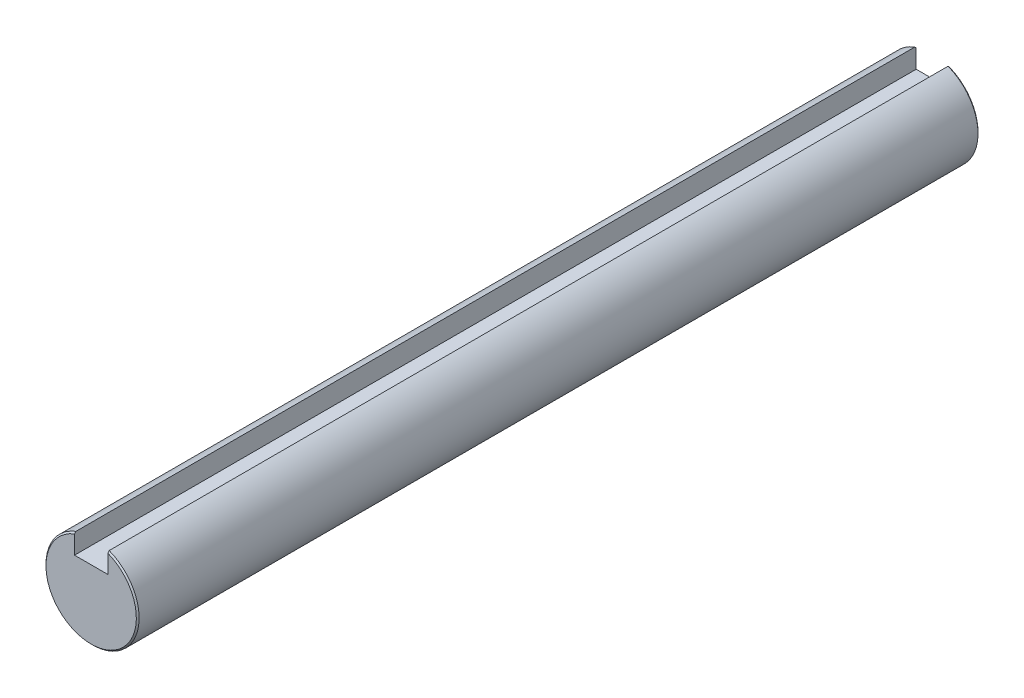
SolidWorks part; units mm, degrees
material "AISI 1045 Steel, cold drawn"
ref_plane "Front Plane" through (0, 0, 0) normal (0, 0, 1) x (1, 0, 0)
ref_plane "Top Plane" through (0, 0, 0) normal (0, 1, 0) x (1, 0, 0)
ref_plane "Right Plane" through (0, 0, 0) normal (1, 0, 0) x (0, 0, -1)
sketch "Sketch1" plane through (0, 0, 0) normal (1, 0, 0) x (0, 0, -1)
  line L0 (0, 0) -> (0, 7) construction
  line L1 (-63.25, 7) -> (63.25, 7)
  line L2 (-63.25, 7) -> (-63.25, -7)
  line L3 (-63.25, -7) -> (63.25, -7)
  line L4 (63.25, 7) -> (63.25, -7)
  line L5 (-63.25, 7) -> (63.25, -7) construction
  line L6 (-63.25, -7) -> (63.25, 7) construction
  line L7 (0, 0) -> (0, -7) construction
  point P0 (0, 0)
  point P8 (-47.15, 7)
  point P10 (47.15, 7)
  point P11 (-63.25, 0)
  dimension "Diameter" = 14
  dimension "Length" = 126.5
  dimension "D1" = 16.1
  dimension "D2" = 16.1
  dimension "Keyway Length" = 126.5
sketch "Sketch2" plane through (0, 0, 0) normal (0, 0, 1) x (1, 0, 0)
  line L0 (0, 0) -> (0, 7) construction
  line L2 (2.5, 3.5383) -> (-2.5, 3.5383)
  line L3 (2.5, 3.5383) -> (2.5, 6.5383)
  line L4 (2.5, 6.5383) -> (-2.5, 6.5383)
  line L5 (-2.5, 3.5383) -> (-2.5, 6.5383)
  line L6 (2.5, 3.5383) -> (-2.5, 6.5383) construction
  line L7 (2.5, 6.5383) -> (-2.5, 3.5383) construction
  circle A0 centre (0, 0) radius 7
  point P3 (0, 5.0383)
  dimension "Keyway Width" = 5
  dimension "Keyway Depth" = 3
sketch "Sketch3" plane through (0, 0, 0) normal (0, 0, 1) x (1, 0, 0)
  line L1 (-2.5, 3.5383) -> (-2.5, 6.5383) construction
  line L2 (2.5, 3.5383) -> (-2.5, 3.5383) construction
  line L3 (2.5, 3.5383) -> (2.5, 6.5383) construction
  line L5 (-2.5, 3.5383) -> (-2.5, 6.5383)
  line L6 (2.5, 3.5383) -> (-2.5, 3.5383)
  line L7 (2.5, 3.5383) -> (2.5, 6.5383)
  circle A0 centre (0, 0) radius 7 construction
  arc A1 (-2.5, 6.5383) -> (2.5, 6.5383) centre (0, 0) ccw
extrude "Boss-Extrude1" add sketch "Sketch3" along normal up to vertex (63.25 mm away) and the other way up to vertex (63.25 mm away) up to point (0, 7, 63.25) other way up to point (0, 7, -63.25)
chamfer "Chamfer1" distance 0.21 angle 45 2 edges at (0, -7, -63.25) (0, -7, 63.25)
equation "\"D2@Sketch1\"=1.15*\"Diameter@Sketch1\""
equation "\"D1@Sketch1\"=\"D2@Sketch1\""
equation "\"D1@Chamfer1\"=\"Diameter@Sketch1\"*.015"
